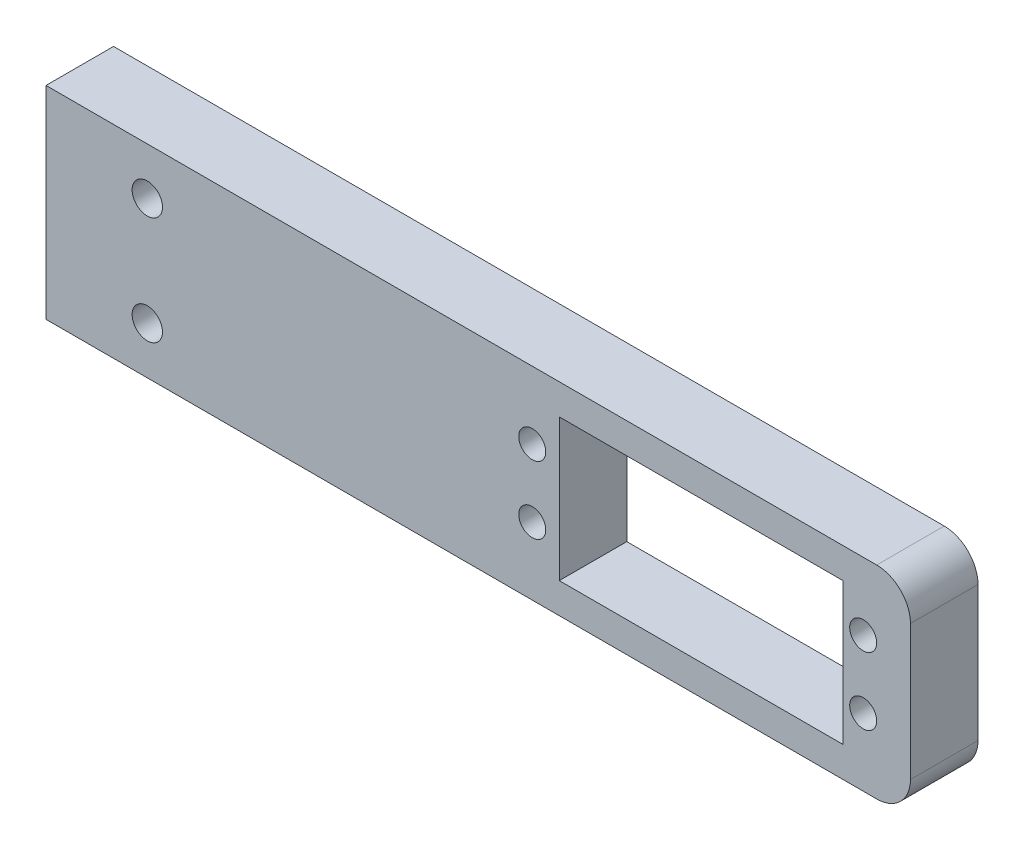
SolidWorks part; units mm, degrees
ref_plane "Plan de face" through (0, 0, 0) normal (0, 0, 1) x (1, 0, 0)
ref_plane "Plan de dessus" through (0, 0, 0) normal (0, 1, 0) x (1, 0, 0)
ref_plane "Plan de droite" through (0, 0, 0) normal (1, 0, 0) x (0, 0, -1)
sketch "Esquisse1" plane through (0, 0, 0) normal (0, 0, 1) x (1, 0, 0)
  line L1 (0, 0) -> (128, 0)
  line L2 (0, 0) -> (0, 30)
  line L3 (0, 30) -> (128, 30)
  line L4 (128, 0) -> (128, 30)
  dimension "D1" = 128
  dimension "D2" = 30
extrude "Boss.-Extru.1" add sketch "Esquisse1" along normal blind 10
sketch "Esquisse2" plane through (0, 0, 0) normal (0, 0, -1) x (-1, 0, 0)
  line L0 (0, 0) -> (-128, 0) construction
  line L1 (-118, 4.5) -> (-76, 4.5)
  line L2 (-118, 4.5) -> (-118, 25.5)
  line L3 (-118, 25.5) -> (-76, 25.5)
  line L4 (-76, 4.5) -> (-76, 25.5)
  line L5 (-128, 0) -> (-128, 30) construction
  circle A0 centre (-121, 10) radius 2
  circle A1 centre (-121, 20) radius 2
  circle A2 centre (-72, 10) radius 2
  circle A3 centre (-72, 20) radius 2
  dimension "D5" = 4
  dimension "D6" = 4
  dimension "D7" = 4
  dimension "D8" = 4
  dimension "D10" = 4
  dimension "D13" = 5.5
  dimension "D1" = 21
  dimension "D2" = 42
  dimension "D3" = 4.5
  dimension "D4" = 10
  dimension "D9" = 4
  dimension "D11" = 3
  dimension "D12" = 3
  dimension "D14" = 5.5
  dimension "D15" = 5.5
  dimension "D16" = 5.5
extrude "Enlèv. mat.-Extru.1" cut sketch "Esquisse2" against normal blind 10
fillet "Congé1" radius 5 2 edges at (128, 0, 5) (128, 30, 5)
sketch "Esquisse4" plane through (0, 0, 10) normal (0, 0, 1) x (1, 0, 0)
  line L0 (123, 30) -> (0, 30) construction
  line L1 (0, 0) -> (123, 0) construction
  line L2 (0, 30) -> (0, 0) construction
  circle A0 centre (15, 23) radius 2.25
  circle A1 centre (15, 7) radius 2.25
  dimension "D1" = 7
  dimension "D3" = 4.5
  dimension "D4" = 4.5
  dimension "D5" = 15
  dimension "D6" = 15
  dimension "D2" = 7
extrude "Enlèv. mat.-Extru.2" cut sketch "Esquisse4" against normal blind 10
